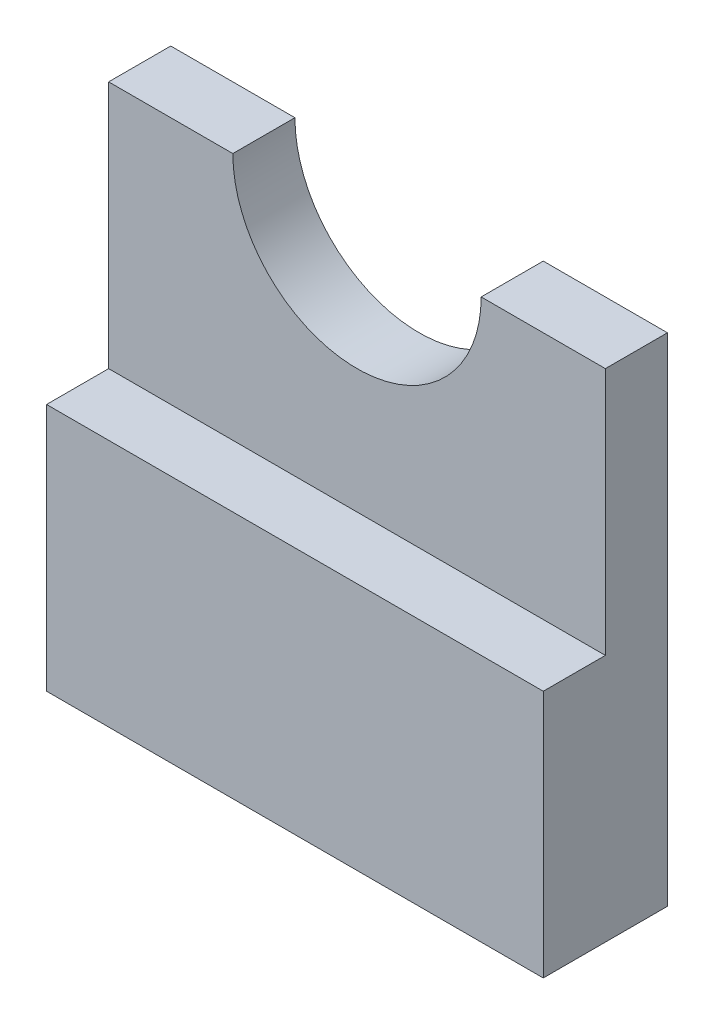
SolidWorks part; units mm, degrees
ref_plane "Front Plane" through (0, 0, 0) normal (0, 0, 1) x (1, 0, 0)
ref_plane "Top Plane" through (0, 0, 0) normal (0, 1, 0) x (1, 0, 0)
ref_plane "Right Plane" through (0, 0, 0) normal (1, 0, 0) x (0, 0, -1)
sketch "Sketch1" plane through (0, 0, 0) normal (0, 0, 1) x (1, 0, 0)
  line L0 (12.7, 25.4) -> (25.4, 25.4)
  line L1 (-25.4, -25.4) -> (25.4, -25.4)
  line L2 (-25.4, -25.4) -> (-25.4, 25.4)
  line L3 (-25.4, 25.4) -> (-12.7, 25.4)
  line L4 (25.4, -25.4) -> (25.4, 25.4)
  line L5 (-25.4, -25.4) -> (25.4, 25.4) construction
  line L6 (-25.4, 25.4) -> (25.4, -25.4) construction
  arc A0 (-12.7, 25.4) -> (12.7, 25.4) centre (0, 25.4) ccw
  point P0 (0, 0)
  dimension "D3" = 12.7
  dimension "D1" = 50.8
  dimension "D2" = 50.8
  dimension "D4" = 25.4
extrude "Boss-Extrude1" add sketch "Sketch1" along normal mid plane 6.35
sketch "Sketch2" plane through (0, 0, 3.175) normal (0, 0, 1) x (1, 0, 0)
  line L0 (25.4, -25.4) -> (25.4, 25.4) construction
  line L1 (-25.4, -25.4) -> (25.4, -25.4)
  line L2 (-25.4, -25.4) -> (-25.4, 0)
  line L3 (-25.4, 0) -> (25.4, 0)
  line L4 (25.4, -25.4) -> (25.4, 0)
extrude "Boss-Extrude2" add sketch "Sketch2" along normal blind 6.35
